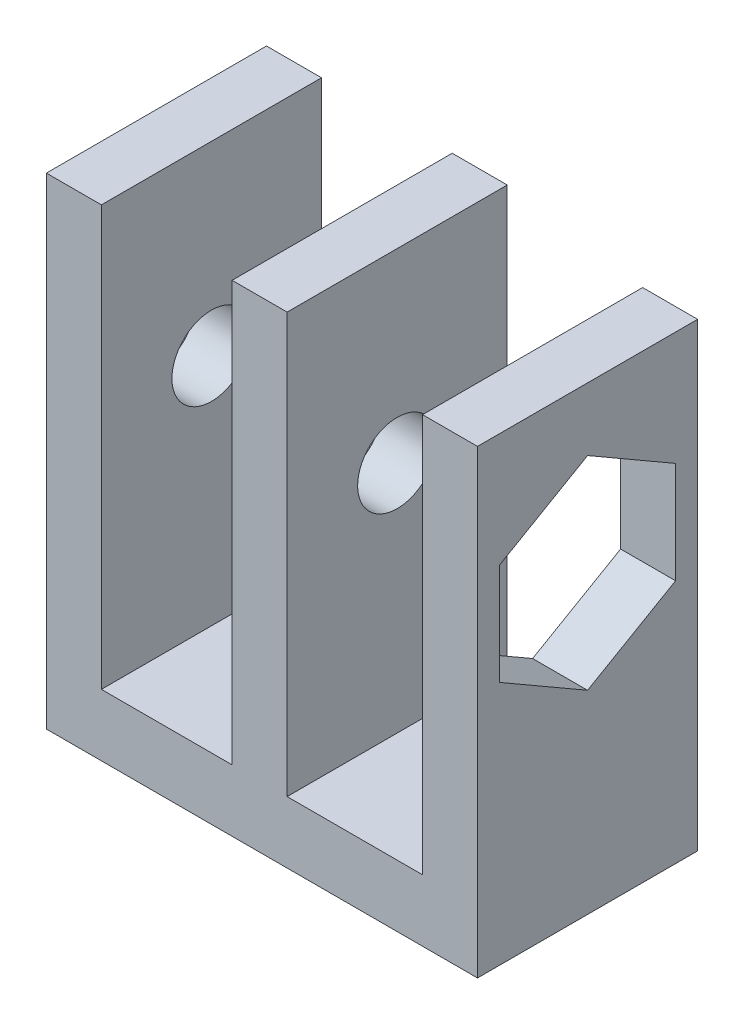
SolidWorks part; units mm, degrees
ref_plane "Front Plane" through (0, 0, 0) normal (0, 0, 1) x (1, 0, 0)
ref_plane "Top Plane" through (0, 0, 0) normal (0, 1, 0) x (1, 0, 0)
ref_plane "Right Plane" through (0, 0, 0) normal (1, 0, 0) x (0, 0, -1)
ref_plane "Plane1"
sketch "Sketch1" plane through (0, 0, 0) normal (0, 0, 1) x (1, 0, 0)
  line L0 (2.032, 17.78) -> (2.032, 2.286)
  line L1 (2.032, 2.286) -> (6.858, 2.286)
  line L2 (6.858, 2.286) -> (6.858, 17.78)
  line L3 (6.858, 17.78) -> (8.89, 17.78)
  line L4 (8.89, 17.78) -> (8.89, 0)
  line L5 (8.89, 0) -> (0, 0)
  line L6 (0, 0) -> (0, 2.1543)
  line L7 (0, 2.1543) -> (0, 17.78)
  line L8 (0, 17.78) -> (2.032, 17.78)
  line L9 (15.24, 0) -> (15.92, 0)
  line L10 (15.92, 0) -> (15.92, 17)
  line L11 (15.92, 17) -> (13.89, 17)
  line L12 (13.89, 17) -> (13.89, 2.286)
  line L13 (13.89, 2.286) -> (8.89, 2.286)
  line L14 (8.89, 2.286) -> (8.89, 0)
  line L15 (8.89, 0) -> (15.24, 0)
  dimension "D1" = 4.826
  dimension "D2" = 2.032
  dimension "D3" = 2.032
  dimension "D4" = 17.78
  dimension "D5" = 2.286
  dimension "D6" = 17
  dimension "D7" = 5
  dimension "D8" = 2.03
  dimension "D9" = 4.826
extrude "Extrusion1" add sketch "Sketch1" along normal blind 8.128 contours L8 L7 L6 L5 L4 L3 L2 L1 L0 | L4 L15 L9 L10 L11 L12 L13
ref_plane "Plane2"
sketch "Sketch2" plane through (8.89, 0, 0) normal (1, 0, 0) x (0, 0, -1)
  line L0 (-8.128, 17.78) -> (0, 17.78) construction
  circle A0 centre (-4.064, 10.922) radius 1.4605
  dimension "D1" = 2.921
  dimension "D2" = 6.858
extrude "Cut-Extrude2" cut sketch "Sketch2" against normal blind 10
sketch "Sketch3" plane through (8.89, 0, 0) normal (1, 0, 0) x (0, 0, -1)
  circle A0 centre (-4.064, 10.922) radius 1.4605
sketch "Sketch4" plane through (15.92, 0, 0) normal (1, 0, 0) x (0, 0, -1)
  line L1 (-4.064, 14.6748) -> (-7.314, 12.7984)
  line L2 (-7.314, 12.7984) -> (-7.314, 9.0456)
  line L3 (-7.314, 9.0456) -> (-4.064, 7.1692)
  line L4 (-4.064, 7.1692) -> (-0.814, 9.0456)
  line L5 (-0.814, 9.0456) -> (-0.814, 12.7984)
  line L6 (-0.814, 12.7984) -> (-4.064, 14.6748)
  circle A0 centre (-4.064, 10.922) radius 3.25 construction
  point P1 (-2.439, 13.7366)
  dimension "D1" = 3.25
extrude "Cut-Extrude3" cut sketch "Sketch4" against normal up to next
